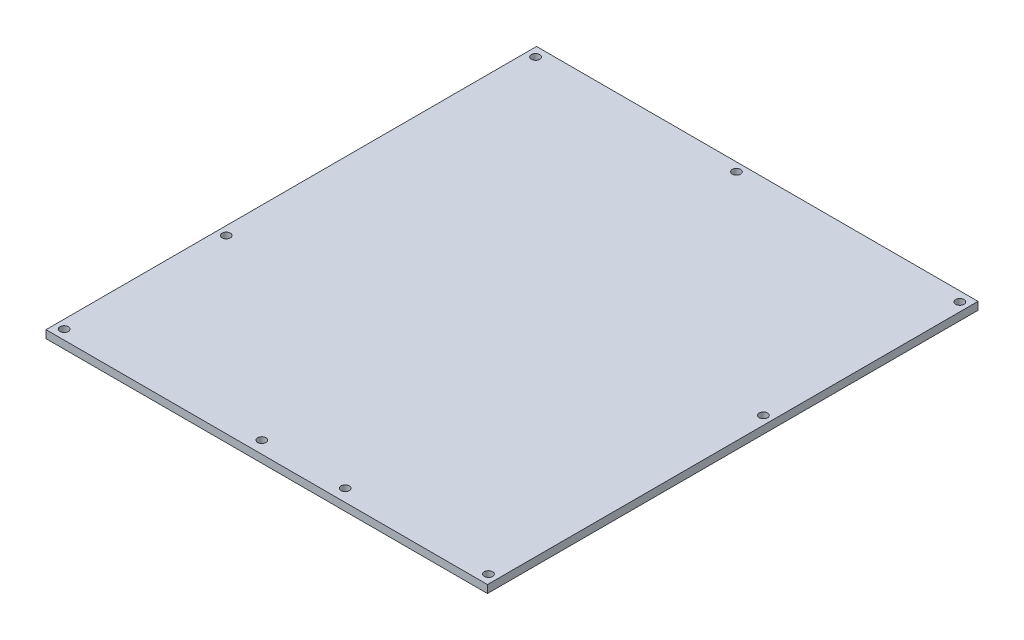
SolidWorks part; units mm, degrees
ref_plane "Front Plane" through (0, 0, 0) normal (0, 0, 1) x (1, 0, 0)
ref_plane "Top Plane" through (0, 0, 0) normal (0, 1, 0) x (1, 0, 0)
ref_plane "Right Plane" through (0, 0, 0) normal (1, 0, 0) x (0, 0, -1)
sketch "Sketch1" plane through (0, 0, 0) normal (0, 1, 0) x (1, 0, 0)
  line L1 (-90, 100) -> (90, 100)
  line L2 (-90, 100) -> (-90, -100)
  line L3 (-90, -100) -> (90, -100)
  line L4 (90, 100) -> (90, -100)
  line L5 (-90, 100) -> (90, -100) construction
  line L6 (-90, -100) -> (90, 100) construction
  circle A0 centre (-86.5, 96.1111) radius 1.7
  circle A1 centre (-5, 96.5) radius 1.7
  circle A2 centre (86.5, 96.1111) radius 1.7
  circle A3 centre (-86.5, -96.1111) radius 1.7
  circle A4 centre (-6.99, -95) radius 1.7
  circle A5 centre (27, -95) radius 1.7
  circle A6 centre (86.5, -96.1111) radius 1.7
  circle A7 centre (86.5, 16) radius 1.7
  circle A8 centre (-86.5, -30) radius 1.7
  point P0 (0, 0)
  dimension "D3" = 3.4
  dimension "D6" = 3.4
  dimension "D9" = 3.4
  dimension "D10" = 3.4
  dimension "D12" = 3.4
  dimension "D15" = 3.4
  dimension "D19" = 3.4
  dimension "D20" = 3.4
  dimension "D23" = 3.4
  dimension "D1" = 180
  dimension "D2" = 200
  dimension "D4" = 3.5
  dimension "D5" = 85
  dimension "D7" = 3.5
  dimension "D8" = 176.5
  dimension "D11" = 3.5
  dimension "D13" = 5
  dimension "D14" = 83.01
  dimension "D16" = 5
  dimension "D17" = 117
  dimension "D18" = 176.5
  dimension "D21" = 116
  dimension "D22" = 3.5
  dimension "D24" = 70
  dimension "D25" = 3.5
extrude "Boss-Extrude1" add sketch "Sketch1" along normal blind 3.175
